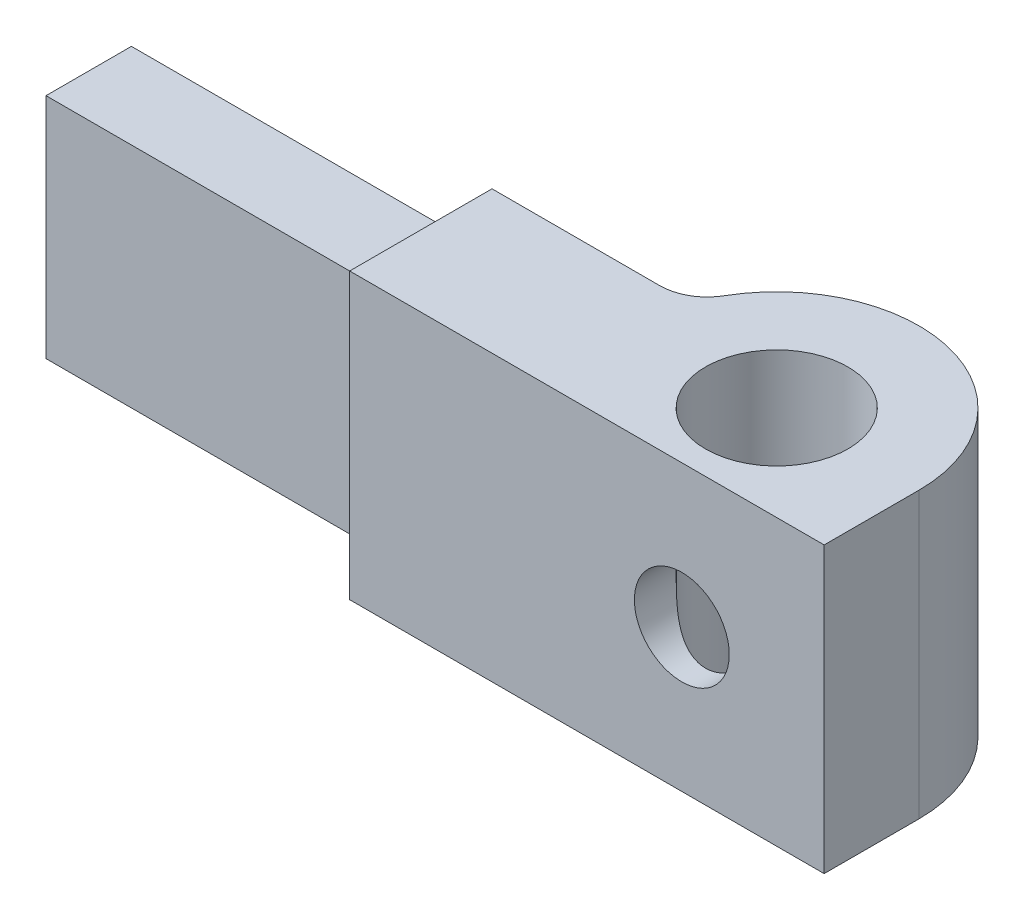
SolidWorks part; units mm, degrees
ref_plane "Front Plane" through (0, 0, 0) normal (0, 0, 1) x (1, 0, 0)
ref_plane "Top Plane" through (0, 0, 0) normal (0, 1, 0) x (1, 0, 0)
ref_plane "Right Plane" through (0, 0, 0) normal (1, 0, 0) x (0, 0, -1)
sketch "Sketch1" plane through (0, 0, 0) normal (0, 0, 1) x (1, 0, 0)
  line L4 (63.5, 38.1) -> (-63.5, 38.1)
  line L5 (63.5, -38.1) -> (63.5, 38.1)
  line L6 (-63.5, -38.1) -> (63.5, -38.1)
  line L7 (-63.5, 38.1) -> (-63.5, -38.1)
  line L8 (63.5, 38.1) -> (-63.5, 38.1)
  line L9 (63.5, -38.1) -> (63.5, 38.1)
  line L10 (-63.5, -38.1) -> (63.5, -38.1)
  line L11 (-63.5, 38.1) -> (-63.5, -38.1)
  circle A1 centre (25.4, 0) radius 12.7
  circle A2 centre (25.4, 0) radius 12.7
  dimension "D1" = 0
  dimension "D2" = 0
sketch "Sketch2" plane through (0, 0, 0) normal (0, 1, 0) x (1, 0, 0)
  line L4 (-63.5, 12.7) -> (-63.5, -25.4)
  line L5 (-63.5, -25.4) -> (63.5, -25.4)
  line L6 (63.5, -25.4) -> (63.5, 0)
  line L7 (-18.5941, 12.7) -> (-63.5, 12.7)
  line L8 (-63.5, 12.7) -> (-63.5, -25.4)
  line L9 (-63.5, -25.4) -> (63.5, -25.4)
  line L10 (63.5, -25.4) -> (63.5, 0)
  line L11 (-18.5941, 12.7) -> (-63.5, 12.7)
  arc A3 (63.5, 0) -> (25.4, 38.1) centre (25.4, 0) ccw
  arc A4 (25.4, 38.1) -> (-7.5956, 19.05) centre (25.4, 0) ccw
  arc A5 (-18.5941, 12.7) -> (-7.5956, 19.05) centre (-18.5941, 25.4) ccw
  arc A6 (63.5, 0) -> (25.4, 38.1) centre (25.4, 0) ccw
  arc A7 (25.4, 38.1) -> (-7.5956, 19.05) centre (25.4, 0) ccw
  arc A8 (-18.5941, 12.7) -> (-7.5956, 19.05) centre (-18.5941, 25.4) ccw
  dimension "D1" = 0
extrude "Boss-Extrude1" add sketch "Sketch2" along normal up to vertex (38.1 mm away) and the other way up to vertex (38.1 mm away)
sketch "Sketch4" plane through (0, 0, 0) normal (0, 0, 1) x (1, 0, 0)
  circle A0 centre (25.4, 0) radius 12.7 construction
  circle A1 centre (25.4, 0) radius 12.7
extrude "Cut-Extrude1" cut sketch "Sketch4" against normal through all both and the other way through all
sketch "Sketch5" plane through (-63.5, 0, 0) normal (-1, 0, 0) x (0, 0, 1)
  line L8 (-5.08, 30.48) -> (-5.08, -30.48)
  line L9 (-5.08, -30.48) -> (17.78, -30.48)
  line L10 (17.78, -30.48) -> (17.78, 30.48)
  line L11 (17.78, 30.48) -> (-5.08, 30.48)
  line L12 (-5.08, 30.48) -> (-5.08, -30.48)
  line L13 (-5.08, -30.48) -> (17.78, -30.48)
  line L14 (17.78, -30.48) -> (17.78, 30.48)
  line L15 (17.78, 30.48) -> (-5.08, 30.48)
  dimension "D1" = 7.62
extrude "Boss-Extrude2" add sketch "Sketch5" along normal blind 88.9
sketch "Sketch6" plane through (0, 38.1, 0) normal (0, 1, 0) x (1, 0, 0)
  line L0 (-63.5, -25.4) -> (63.5, -25.4) construction
  circle A0 centre (25.4, 0) radius 19.05
  dimension "D1" = 6.35
extrude "Cut-Extrude2" cut sketch "Sketch6" against normal through all
